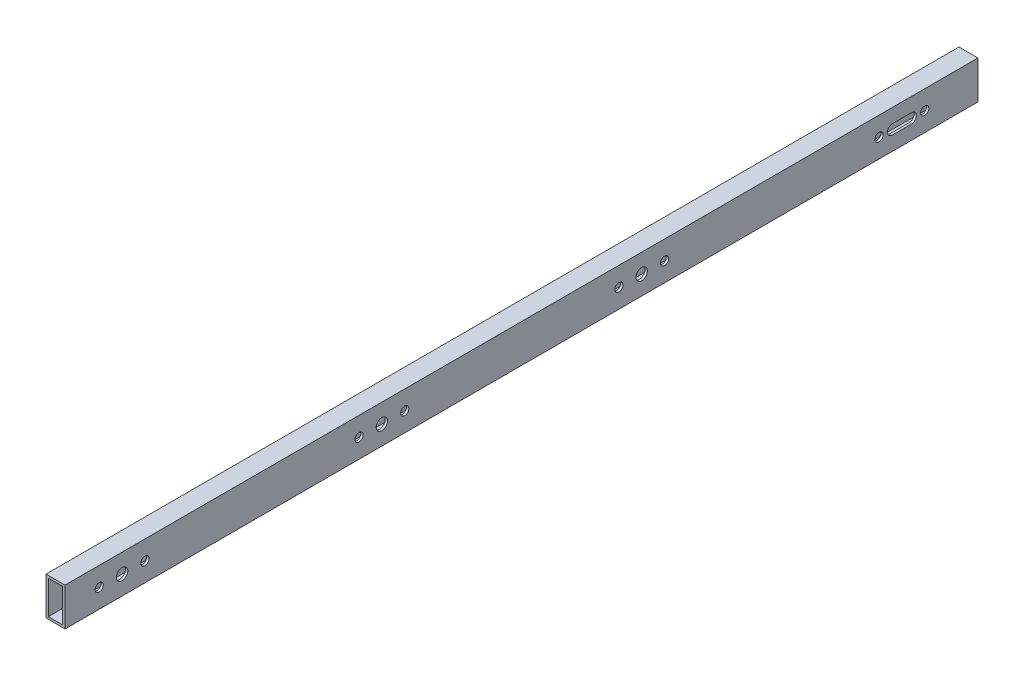
SolidWorks part; units mm, degrees
ref_plane "Front Plane" through (0, 0, 0) normal (0, 0, 1) x (1, 0, 0)
ref_plane "Top Plane" through (0, 0, 0) normal (0, 1, 0) x (1, 0, 0)
ref_plane "Right Plane" through (0, 0, 0) normal (1, 0, 0) x (0, 0, -1)
sketch "Sketch1" plane through (0, 0, 0) normal (0, 0, 1) x (1, 0, 0)
  line L1 (-6.35, -12.7) -> (6.35, -12.7)
  line L2 (-6.35, -12.7) -> (-6.35, 12.7)
  line L3 (-6.35, 12.7) -> (6.35, 12.7)
  line L4 (6.35, -12.7) -> (6.35, 12.7)
  line L6 (-6.35, 12.7) -> (6.35, -12.7) construction
  line L7 (-4.7625, -11.1125) -> (4.7625, -11.1125)
  line L8 (-4.7625, -11.1125) -> (-4.7625, 11.1125)
  line L9 (-4.7625, 11.1125) -> (4.7625, 11.1125)
  line L10 (4.7625, -11.1125) -> (4.7625, 11.1125)
  line L11 (-4.7625, -11.1125) -> (4.7625, 11.1125) construction
  line L12 (-4.7625, 11.1125) -> (4.7625, -11.1125) construction
  point P0 (0, 0)
  point P6 (0, 0)
  dimension "D1" = 25.4
  dimension "D2" = 1.5875
  dimension "D3" = 12.7
  dimension "D4" = 1.5875
  dimension "D5" = 1.5875
extrude "Boss-Extrude1" add sketch "Sketch1" along normal blind 609.6
sketch "Sketch2" plane through (6.35, 0, 0) normal (1, 0, 0) x (0, 0, -1)
  line L0 (-609.6, 0) -> (0, 0) construction
  line L1 (-609.6, -12.7) -> (-609.6, 12.7) construction
  line L2 (-571.5, 12.7) -> (-571.5, -12.7) construction
  line L3 (-44.45, 0) -> (-57.15, 0) construction
  line L4 (-44.45, -3.302) -> (-57.15, -3.302)
  line L5 (-44.45, 3.302) -> (-57.15, 3.302)
  line L6 (-609.6, 12.7) -> (0, 12.7) construction
  line L7 (-609.6, -12.7) -> (0, -12.7) construction
  line L8 (-50.8, 12.7) -> (-50.8, -12.7) construction
  circle A0 centre (-571.5, 0) radius 3.81
  arc A2 (-44.45, -3.302) -> (-44.45, 3.302) centre (-44.45, 0) ccw
  arc A3 (-57.15, 3.302) -> (-57.15, -3.302) centre (-57.15, 0) ccw
  circle A4 centre (-586.74, 0) radius 2.75
  circle A5 centre (-556.26, 0) radius 2.75
  circle A6 centre (-66.04, 0) radius 2.75
  circle A8 centre (-35.56, 0) radius 2.75
  circle A9 centre (-382.778, 0) radius 2.75
  circle A10 centre (-398.018, 0) radius 3.81
  circle A11 centre (-413.258, 0) radius 2.75
  circle A12 centre (-209.296, 0) radius 2.75
  circle A13 centre (-224.536, 0) radius 3.81
  circle A14 centre (-239.776, 0) radius 2.75
  point P9 (-50.8, 0)
  point P30 (0, 0)
  dimension "D1" = 7.62
  dimension "D2" = 3.302
  dimension "D6" = 5.5
  dimension "D8" = 30.48
  dimension "D3" = 38.1
  dimension "D4" = 12.7
  dimension "D5" = 520.7
  dimension "D7" = 30.48
  dimension "D10" = 173.482
  dimension "D9" = 3
extrude "Cut-Extrude1" cut sketch "Sketch2" against normal through all
sketch "Sketch3" plane through (0, 0, 609.6) normal (0, 0, 1) x (1, 0, 0)
  line L0 (-6.35, 12.7) -> (-6.35, -12.7) construction
  line L1 (-4.7625, 11.1125) -> (-6.35, 11.1125)
  line L2 (-4.7625, 11.1125) -> (-4.7625, -11.1125)
  line L3 (-4.7625, -11.1125) -> (-6.35, -11.1125)
  line L4 (-6.35, 11.1125) -> (-6.35, -11.1125)
  line L5 (-4.7625, -11.1125) -> (4.7625, -11.1125) construction
sketch "Sketch4" plane through (-6.35, 0, 0) normal (-1, 0, 0) x (0, 0, 1)
  line L0 (35.56, 0) -> (66.04, 0) construction
  line L1 (35.56, 5) -> (66.04, 5)
  line L2 (35.56, -5) -> (66.04, -5)
  line L3 (556.26, 0) -> (586.74, 0) construction
  line L4 (556.26, 5) -> (586.74, 5)
  line L5 (556.26, -5) -> (586.74, -5)
  line L6 (209.042, 0) -> (239.522, 0) construction
  line L7 (209.042, 5) -> (239.522, 5)
  line L8 (209.042, -5) -> (239.522, -5)
  line L9 (382.524, 0) -> (413.004, 0) construction
  line L10 (382.524, 5) -> (413.004, 5)
  line L11 (382.524, -5) -> (413.004, -5)
  arc A0 (35.56, 5) -> (35.56, -5) centre (35.56, 0) ccw
  arc A1 (66.04, -5) -> (66.04, 5) centre (66.04, 0) ccw
  arc A2 (556.26, 5) -> (556.26, -5) centre (556.26, 0) ccw
  arc A3 (586.74, -5) -> (586.74, 5) centre (586.74, 0) ccw
  arc A4 (209.042, 5) -> (209.042, -5) centre (209.042, 0) ccw
  arc A5 (239.522, -5) -> (239.522, 5) centre (239.522, 0) ccw
  arc A6 (382.524, 5) -> (382.524, -5) centre (382.524, 0) ccw
  arc A7 (413.004, -5) -> (413.004, 5) centre (413.004, 0) ccw
  point P2 (50.8, 0)
  point P13 (571.5, 0)
  point P22 (224.282, 0)
  point P29 (397.764, 0)
  dimension "D1" = 5
  dimension "D3" = 173.482
  dimension "D2" = 3
extrude "Cut-Extrude3" cut sketch "Sketch4" against normal up to next
sketch "Sketch5" plane through (0, -12.7, 0) normal (0, -1, 0) x (1, 0, 0)
  line L0 (-6.35, 609.6) -> (6.35, 609.6) construction
  line L1 (0, 609.6) -> (0, 0) construction
  line L2 (-6.35, 304.8) -> (6.35, 304.8) construction
  line L3 (-6.35, 609.6) -> (-6.35, 0) construction
  line L4 (6.35, 609.6) -> (6.35, 0) construction
  circle A0 centre (0, 596.9) radius 2.75
  circle A1 centre (0, 12.7) radius 2.75
  dimension "D1" = 5.5
  dimension "D2" = 12.7
extrude "Cut-Extrude5" cut sketch "Sketch5" against normal up to next
